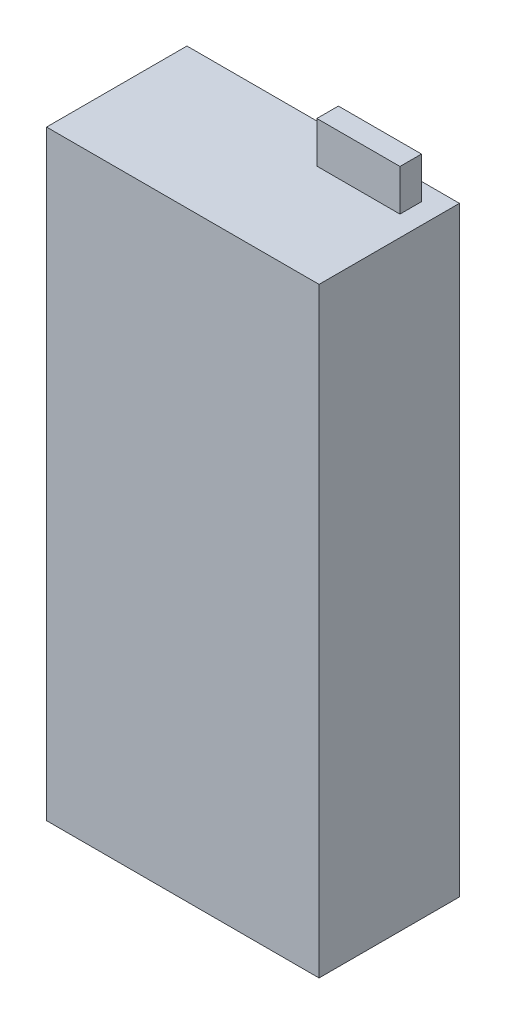
SolidWorks part; units mm, degrees
ref_plane "前视基准面" through (0, 0, 0) normal (0, 0, 1) x (1, 0, 0)
ref_plane "上视基准面" through (0, 0, 0) normal (0, 1, 0) x (1, 0, 0)
ref_plane "右视基准面" through (0, 0, 0) normal (1, 0, 0) x (0, 0, -1)
sketch "草图1" plane through (0, 0, 0) normal (0, 0, 1) x (1, 0, 0)
  line L1 (-193.0746, 287.1493) -> (-61.0746, 287.1493)
  line L2 (-193.0746, 287.1493) -> (-193.0746, -3.8507)
  line L3 (-193.0746, -3.8507) -> (-61.0746, -3.8507)
  line L4 (-61.0746, 287.1493) -> (-61.0746, -3.8507)
  line L5 (-193.0746, 287.1493) -> (-61.0746, -3.8507) construction
  line L6 (-193.0746, -3.8507) -> (-61.0746, 287.1493) construction
  point P0 (-127.0746, 141.6493)
  dimension "D1" = 132
  dimension "D2" = 291
extrude "凸台-拉伸1" add sketch "草图1" along normal blind 68
sketch "草图2" plane through (-193.0746, 0, 0) normal (-1, 0, 0) x (0, 0, 1)
  line L0 (34, -3.8507) -> (34, 287.1493) construction
  line L1 (68, -3.8507) -> (0, -3.8507) construction
  line L2 (68, 287.1493) -> (0, 287.1493) construction
  line L3 (17.5, 23.1493) -> (55.5, 23.1493) construction
  line L4 (55.5, 23.1493) -> (55.5, 33.1493) construction
  line L5 (55.5, 28.1493) -> (47.2032, 28.1493) construction
  line L6 (47.2032, 28.1493) -> (47.2032, 264.4493) construction
  line L7 (47.2032, 146.2993) -> (37.4688, 146.2993) construction
  line L8 (68, 287.1493) -> (68, -3.8507) construction
  circle A0 centre (17.5, 23.1493) radius 2
  circle A1 centre (55.5, 23.1493) radius 2
  circle A2 centre (55.5, 33.1493) radius 2
  circle A3 centre (17.5, 33.1493) radius 2
  circle A4 centre (17.5, 269.4493) radius 2
  circle A5 centre (17.5, 259.4493) radius 2
  circle A6 centre (55.5, 259.4493) radius 2
  circle A7 centre (55.5, 269.4493) radius 2
  point P29 (0, 0)
  point P30 (17.5, 29.3577)
  dimension "D1" = 12.5
  dimension "D2" = 10
  dimension "D3" = 38
  dimension "D4" = 27
  dimension "D5" = 10
  dimension "D6" = 236.3
extrude "切除-拉伸1" cut sketch "草图2" against normal blind 4
sketch "草图3" plane through (0, -3.8507, 0) normal (0, -1, 0) x (1, 0, 0)
  line L1 (-178.5983, 24.2214) -> (-125.5451, 24.2214)
  line L2 (-178.5983, 24.2214) -> (-178.5983, 14.0192)
  line L3 (-178.5983, 14.0192) -> (-125.5451, 14.0192)
  line L4 (-125.5451, 24.2214) -> (-125.5451, 14.0192)
extrude "凸台-拉伸2" add sketch "草图3" along normal blind 20
sketch "草图4" plane through (0, -3.8507, 0) normal (0, -1, 0) x (1, 0, 0)
  circle A0 centre (-94.2519, 37.5872) radius 24.1206
extrude "凸台-拉伸3" add sketch "草图4" along normal blind 5
sketch "草图5" plane through (0, 287.1493, 0) normal (0, 1, 0) x (1, 0, 0)
  line L1 (-70.9484, -18.9316) -> (-111.2022, -18.9316)
  line L2 (-70.9484, -18.9316) -> (-70.9484, -8.5092)
  line L3 (-70.9484, -8.5092) -> (-111.2022, -8.5092)
  line L4 (-111.2022, -18.9316) -> (-111.2022, -8.5092)
extrude "凸台-拉伸4" add sketch "草图5" along normal blind 20
